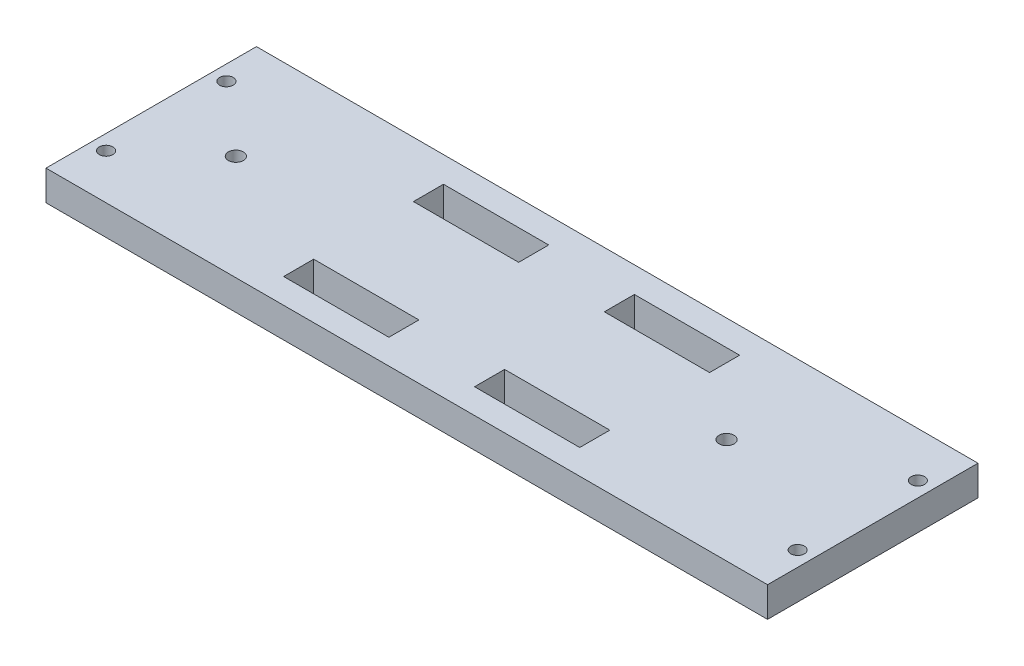
SolidWorks part; units mm, degrees
material "ABS"
ref_plane "Alzado" through (0, 0, 0) normal (0, 0, 1) x (1, 0, 0)
ref_plane "Planta" through (0, 0, 0) normal (0, 1, 0) x (1, 0, 0)
ref_plane "Vista lateral" through (0, 0, 0) normal (1, 0, 0) x (0, 0, -1)
sketch "Croquis1" plane through (0, 0, 0) normal (0, 1, 0) x (1, 0, 0)
  line L1 (-120, -35) -> (120, -35)
  line L2 (-120, -35) -> (-120, 35)
  line L3 (-120, 35) -> (120, 35)
  line L4 (120, -35) -> (120, 35)
  line L5 (-120, -35) -> (120, 35) construction
  line L6 (-120, 35) -> (120, -35) construction
  point P0 (0, 0)
  dimension "D1" = 240
  dimension "D2" = 70
extrude "Saliente-Extruir1" add sketch "Croquis1" along normal mid plane 10
sketch "Croquis2" plane through (0, 5, 0) normal (0, 1, 0) x (1, 0, 0)
  line L0 (-115, 35) -> (-115, 20) construction
  line L1 (120, 35) -> (-120, 35) construction
  line L2 (-115, 20) -> (-115, -20) construction
  line L3 (-115, -20) -> (-115, -35) construction
  line L4 (-120, -35) -> (120, -35) construction
  line L5 (-120, 35) -> (-120, -35) construction
  line L6 (0, -5.5) -> (0, 5.5) construction
  circle A0 centre (-115, 20) radius 2.25
  circle A1 centre (-115, -20) radius 2.25
  circle A2 centre (115, -20) radius 2.25
  circle A3 centre (115, 20) radius 2.25
  dimension "D3" = 4.5
  dimension "D1" = 40
  dimension "D2" = 5
extrude "Cortar-Extruir1" cut sketch "Croquis2" against normal through all
sketch "Croquis3" plane through (0, 5, 0) normal (0, 1, 0) x (1, 0, 0)
  line L0 (57.5, 0) -> (-57.5, 0) construction
  line L1 (-91, 0) -> (-24, 0) construction
  line L2 (-91, 4) -> (-24, 4)
  line L3 (-91, -4) -> (-24, -4)
  line L4 (91, 0) -> (24, 0) construction
  line L5 (91, -4) -> (24, -4)
  line L6 (91, 4) -> (24, 4)
  line L7 (0, -17.5) -> (0, 17.5) construction
  line L8 (0, 14) -> (0, 21) construction
  line L9 (-4, 14) -> (-4, 21)
  line L10 (4, 14) -> (4, 21)
  line L11 (0, -14) -> (0, -21) construction
  line L12 (4, -14) -> (4, -21)
  line L13 (-4, -14) -> (-4, -21)
  line L14 (-120, 35) -> (-120, -35) construction
  line L15 (120, 35) -> (-120, 35) construction
  arc A0 (-91, 4) -> (-91, -4) centre (-91, 0) ccw
  arc A1 (-24, -4) -> (-24, 4) centre (-24, 0) ccw
  arc A2 (91, -4) -> (91, 4) centre (91, 0) ccw
  arc A3 (24, 4) -> (24, -4) centre (24, 0) ccw
  arc A4 (-4, 14) -> (4, 14) centre (0, 14) ccw
  arc A5 (4, 21) -> (-4, 21) centre (0, 21) ccw
  arc A6 (4, -14) -> (-4, -14) centre (0, -14) ccw
  arc A7 (-4, -21) -> (4, -21) centre (0, -21) ccw
  point P3 (0, 10)
  point P4 (0, 0)
  point P7 (-57.5, 0)
  point P13 (57.5, 0)
  point P22 (0, 0)
  point P24 (0, 17.5)
  point P30 (0, -17.5)
  point P37 (-20, 0)
  point P39 (0, 25)
  point P42 (-95, 0)
  dimension "D1" = 10
  dimension "D2" = 20
  dimension "D3" = 8
  dimension "D4" = 25
  dimension "D5" = 8
  dimension "D6" = 10
extrude "Cortar-Extruir2" [suppressed] cut sketch "Croquis3" against normal through all
sketch "Croquis4" [suppressed] plane through (0, 5, 0) normal (0, 1, 0) x (1, 0, 0)
  line L0 (4, 17.5) -> (57.5, 17.5) construction
  line L2 (4, 14) -> (4, 21) construction
  line L4 (57.5, 17.5) -> (57.5, 4) construction
  line L9 (91, 4) -> (24, 4) construction
  line L10 (57.5, 14) -> (57.5, 21) construction
  line L11 (53.5, 14) -> (53.5, 21)
  line L12 (61.5, 14) -> (61.5, 21)
  line L13 (0, 25) -> (57.5, 25) construction
  line L14 (-5.5, 0) -> (5.5, 0) construction
  line L15 (57.5, -14) -> (57.5, -21) construction
  line L16 (53.5, -14) -> (53.5, -21)
  line L17 (61.5, -14) -> (61.5, -21)
  line L18 (0, -5.5) -> (0, 5.5) construction
  line L19 (-57.5, 14) -> (-57.5, 21) construction
  line L20 (-53.5, 14) -> (-53.5, 21)
  line L21 (-61.5, 14) -> (-61.5, 21)
  line L22 (-57.5, -14) -> (-57.5, -21) construction
  line L23 (-53.5, -14) -> (-53.5, -21)
  line L24 (-61.5, -14) -> (-61.5, -21)
  arc A2 (53.5, 14) -> (61.5, 14) centre (57.5, 14) ccw
  arc A3 (61.5, 21) -> (53.5, 21) centre (57.5, 21) ccw
  arc A4 (4, 21) -> (-4, 21) centre (0, 21) ccw construction
  arc A5 (53.5, -14) -> (61.5, -14) centre (57.5, -14) cw
  arc A6 (61.5, -21) -> (53.5, -21) centre (57.5, -21) cw
  arc A7 (-53.5, 14) -> (-61.5, 14) centre (-57.5, 14) cw
  arc A8 (-61.5, 21) -> (-53.5, 21) centre (-57.5, 21) cw
  arc A9 (-53.5, -14) -> (-61.5, -14) centre (-57.5, -14) ccw
  arc A10 (-61.5, -21) -> (-53.5, -21) centre (-57.5, -21) ccw
  point P9 (57.5, 17.5)
  point P23 (57.5, -17.5)
  point P32 (-57.5, 17.5)
  point P39 (-57.5, -17.5)
  dimension "D1" = 8
extrude "Cortar-Extruir3" [suppressed] cut sketch "Croquis4" against normal through all
sketch "Croquis5" plane through (0, 5, 0) normal (0, 1, 0) x (1, 0, 0)
  line L0 (-31.75, 35) -> (-31.75, 21.46) construction
  line L1 (120, 35) -> (-120, 35) construction
  line L2 (-31.75, 21.46) -> (-31.75, -21.71) construction
  line L3 (-31.75, -21.71) -> (-31.75, -35) construction
  line L4 (-120, -35) -> (120, -35) construction
  line L5 (-120, 35) -> (-120, -35) construction
  line L6 (-49.25, 16.46) -> (-14.25, 16.46)
  line L7 (-49.25, 16.46) -> (-49.25, 26.46)
  line L8 (-49.25, 26.46) -> (-14.25, 26.46)
  line L9 (-14.25, 16.46) -> (-14.25, 26.46)
  line L10 (-49.25, 16.46) -> (-14.25, 26.46) construction
  line L11 (-49.25, 26.46) -> (-14.25, 16.46) construction
  line L12 (-49.25, -26.71) -> (-14.25, -26.71)
  line L13 (-49.25, -26.71) -> (-49.25, -16.71)
  line L14 (-49.25, -16.71) -> (-14.25, -16.71)
  line L15 (-14.25, -26.71) -> (-14.25, -16.71)
  line L16 (-49.25, -26.71) -> (-14.25, -16.71) construction
  line L17 (-49.25, -16.71) -> (-14.25, -26.71) construction
  line L18 (14.25, 16.46) -> (14.25, 26.46)
  line L19 (14.25, 16.46) -> (49.25, 16.46)
  line L20 (49.25, 16.46) -> (49.25, 26.46)
  line L21 (14.25, 26.46) -> (49.25, 26.46)
  line L22 (14.25, -26.71) -> (14.25, -16.71)
  line L23 (14.25, -26.71) -> (49.25, -26.71)
  line L24 (49.25, -26.71) -> (49.25, -16.71)
  line L25 (14.25, -16.71) -> (49.25, -16.71)
  dimension "D1" = 13.54
  dimension "D2" = 13.29
  dimension "D3" = 35
  dimension "D4" = 10
  dimension "D5" = 88.25
  dimension "D7" = 28.5
  dimension "D6" = 2
extrude "Cortar-Extruir4" cut sketch "Croquis5" against normal through all
sketch "Croquis6" plane through (0, 5, 0) normal (0, 1, 0) x (1, 0, 0)
  line L0 (120, 0) -> (71.38, 0) construction
  line L1 (120, -35) -> (120, 35) construction
  line L2 (-120, 0) -> (-91.85, 0) construction
  line L3 (-120, 35) -> (-120, -35) construction
  circle A0 centre (71.38, 0) radius 2.5
  circle A1 centre (-91.85, 0) radius 2.5
  dimension "D2" = 5
  dimension "D1" = 48.62
  dimension "D3" = 28.15
extrude "Cortar-Extruir5" cut sketch "Croquis6" against normal through all
